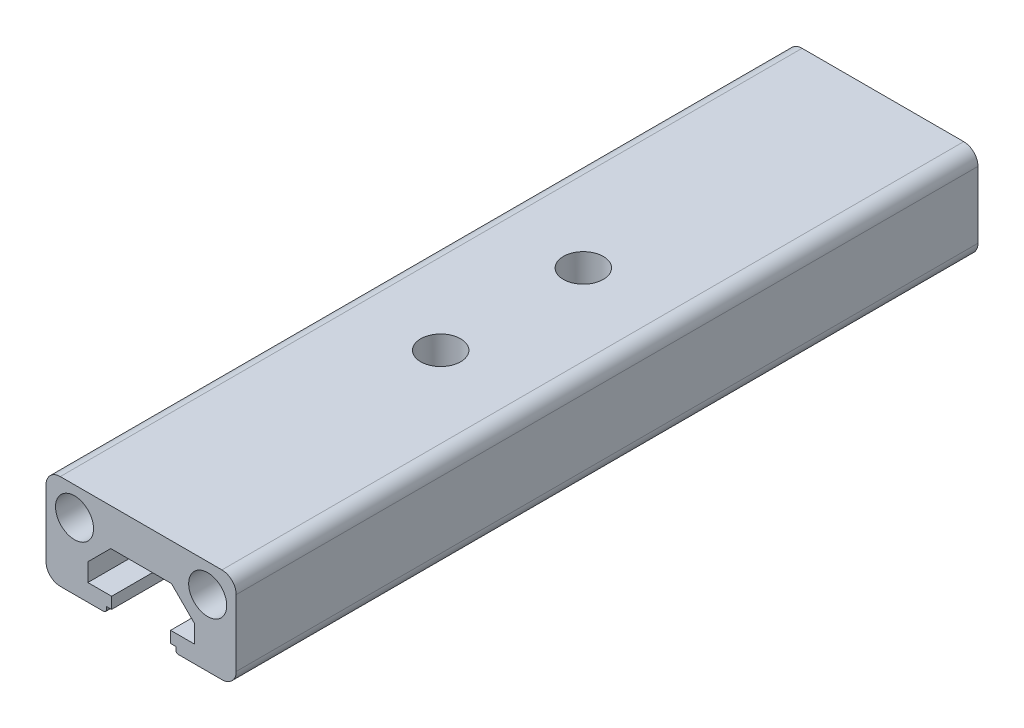
SolidWorks part; units mm, degrees
ref_plane "前视基准面" through (0, 0, 0) normal (0, 0, 1) x (1, 0, 0)
ref_plane "上视基准面" through (0, 0, 0) normal (0, 1, 0) x (1, 0, 0)
ref_plane "右视基准面" through (0, 0, 0) normal (1, 0, 0) x (0, 0, -1)
sketch "草图1" plane through (0, 0, 0) normal (0, 0, 1) x (1, 0, 0)
  line L0 (-8.5, 0) -> (-3.95, 0)
  line L1 (-3.65, 0.3) -> (-3.65, 0.6)
  line L2 (-3.65, 0.6) -> (-3.1, 0.6)
  line L3 (-3.1, 0.6) -> (-3.1, 1.8)
  line L4 (-3.1, 1.8) -> (-5.6, 1.8)
  line L5 (-5.6, 1.8) -> (-5.6, 3.6929)
  line L6 (-5.6, 3.6929) -> (-3.1929, 6.1)
  line L7 (-3.1929, 6.1) -> (3.1929, 6.1)
  line L8 (0, 6.1) -> (0, 10) construction
  line L9 (8.5, 10) -> (-8.5, 10)
  line L10 (-10, 8.5) -> (-10, 1.5)
  line L11 (0, 6.1) -> (0, 0) construction
  line L12 (0, 10) -> (-10, 0) construction
  line L13 (5.6, 3.6929) -> (3.1929, 6.1)
  line L14 (5.6, 1.8) -> (5.6, 3.6929)
  line L15 (3.1, 1.8) -> (5.6, 1.8)
  line L16 (3.1, 0.6) -> (3.1, 1.8)
  line L17 (3.65, 0.6) -> (3.1, 0.6)
  line L18 (3.65, 0.3) -> (3.65, 0.6)
  line L19 (8.5, 0) -> (3.95, 0)
  line L20 (10, 8.5) -> (10, 1.5)
  circle A0 centre (-7, 7) radius 2
  arc A1 (-8.5, 0) -> (-10, 1.5) centre (-8.5, 1.5) cw
  arc A2 (-8.5, 10) -> (-10, 8.5) centre (-8.5, 8.5) ccw
  arc A3 (8.5, 0) -> (10, 1.5) centre (8.5, 1.5) ccw
  arc A4 (8.5, 10) -> (10, 8.5) centre (8.5, 8.5) cw
  circle A5 centre (7, 7) radius 2
  arc A6 (3.65, 0.3) -> (3.95, 0) centre (3.95, 0.3) ccw
  arc A7 (-3.95, 0) -> (-3.65, 0.3) centre (-3.95, 0.3) ccw
  point P37 (3.65, 0)
  point P40 (-3.65, 0)
  dimension "D10" = 14
  dimension "D11" = 3
  dimension "D12" = 4
  dimension "D14" = 1.5
  dimension "D15" = 0.3
  dimension "D1" = 20
  dimension "D2" = 1.2
  dimension "D3" = 1.8
  dimension "D4" = 10
  dimension "D5" = 6.2
  dimension "D6" = 7.3
  dimension "D7" = 3.9
  dimension "D8" = 11.2
  dimension "D9" = 45
  dimension "D13" = 0.5
extrude "凸台-拉伸1" add sketch "草图1" along normal mid plane 78
sketch "草图2" plane through (0, 10, 0) normal (0, 1, 0) x (1, 0, 0)
  line L0 (0, -7.5) -> (0, 7.5) construction
  circle A0 centre (0, 7.5) radius 2.1
  circle A1 centre (0, -7.5) radius 2.1
  point P4 (0, 0)
  dimension "D1" = 4.2
  dimension "D2" = 15
extrude "切除-拉伸1" cut sketch "草图2" against normal through all and the other way through all
